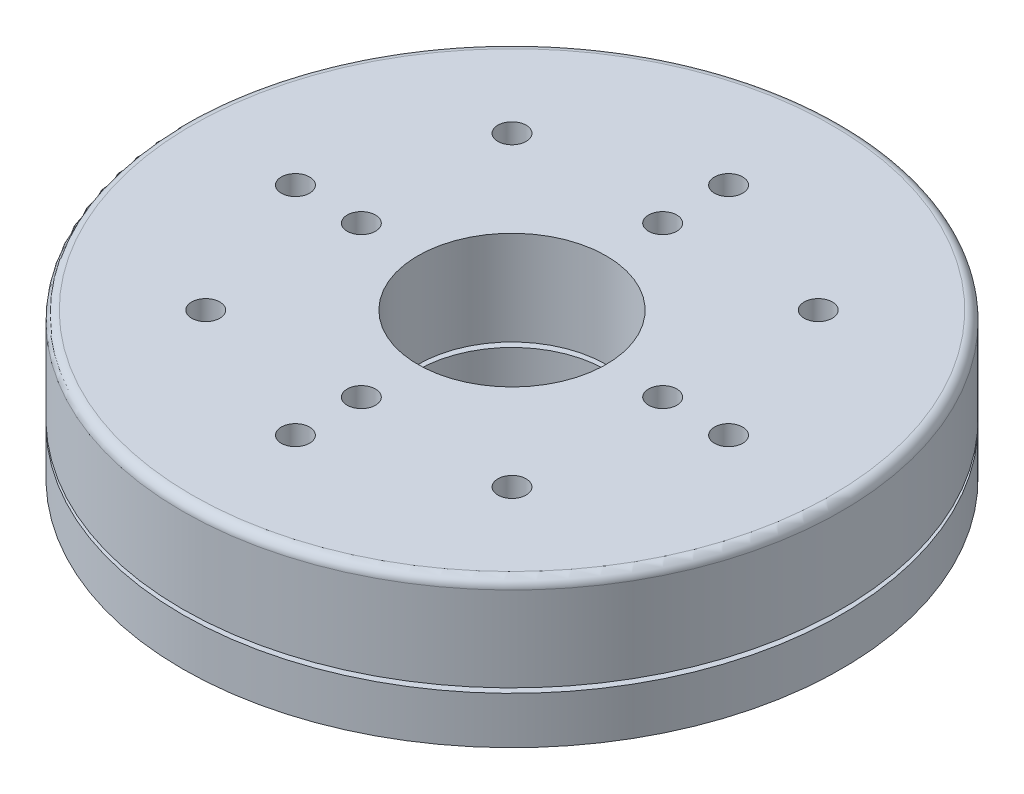
SolidWorks part; units mm, degrees
ref_plane "Front" through (0, 0, 0) normal (0, 0, 1) x (1, 0, 0)
ref_plane "Top" through (0, 0, 0) normal (0, 1, 0) x (1, 0, 0)
ref_plane "Right" through (0, 0, 0) normal (1, 0, 0) x (0, 0, -1)
sketch "草图1" plane through (0, 0, 0) normal (0, 1, 0) x (1, 0, 0)
  circle A0 centre (0, 0) radius 35
  dimension "D1" = 70
extrude "凸台-拉伸1" add sketch "草图1" along normal blind 10
fillet "圆角1" radius 1 1 edges at (0, 10, 35)
ref_plane "基准面1" through (0, -0.5, 0) normal (0, -1, 0) x (-1, 0, 0)
sketch "草图2" plane through (0, -0.5, 0) normal (0, -1, 0) x (-1, 0, 0)
  circle A0 centre (0, 0) radius 35
  dimension "D1" = 70
extrude "凸台-拉伸2" add sketch "草图2" along normal blind 5 separate body
sketch "草图3" plane through (0, 10, 0) normal (0, 1, 0) x (1, 0, 0)
  line L0 (0, 0) -> (12.5, 0) construction
  line L1 (0, 0) -> (8.8388, -8.8388) construction
  line L2 (0, 0) -> (0, 5.9913) construction
  line L3 (0, 0) -> (8.8388, 8.8388) construction
  line L4 (0.001, 0) -> (0, 0) construction
  line L5 (0, 0) -> (-23, 0) construction
  circle A0 centre (0, 0) radius 16 construction
  circle A1 centre (0, 0) radius 23 construction
  circle A2 centre (-23, 0) radius 1.5
  circle A3 centre (-16, 0) radius 1.5
  circle A4 centre (0.001, 0.001) radius 23 construction
  circle A5 centre (0.001, 16.001) radius 1.5
  circle A6 centre (0.002, 0) radius 23 construction
  circle A7 centre (16.002, 0) radius 1.5
  circle A8 centre (0.001, -0.001) radius 23 construction
  circle A9 centre (0.001, -16.001) radius 1.5
  circle A10 centre (-16.2635, 16.2635) radius 1.5
  circle A11 centre (0, 23) radius 1.5
  circle A12 centre (16.2635, 16.2635) radius 1.5
  circle A13 centre (23, 0) radius 1.5
  circle A17 centre (16.2635, -16.2635) radius 1.5
  circle A18 centre (0, -23) radius 1.5
  circle A19 centre (-16.2635, -16.2635) radius 1.5
  dimension "D1" = 45
  dimension "D3" = 46
  dimension "D7" = 4
  dimension "D8" = 0.001
  dimension "D9" = 8
  dimension "D5" = 3
  dimension "D4" = 32
  dimension "D6" = 3
  dimension "D2" = 45
  dimension "D10" = 23
extrude "切除-拉伸1" cut sketch "草图3" against normal blind 5
sketch "草图5" plane through (0, -0.5, 0) normal (0, -1, 0) x (-1, 0, 0)
  circle A0 centre (0, 0) radius 10
  dimension "D1" = 20
extrude "切除-拉伸3" cut sketch "草图5" against normal through all and the other way through all
